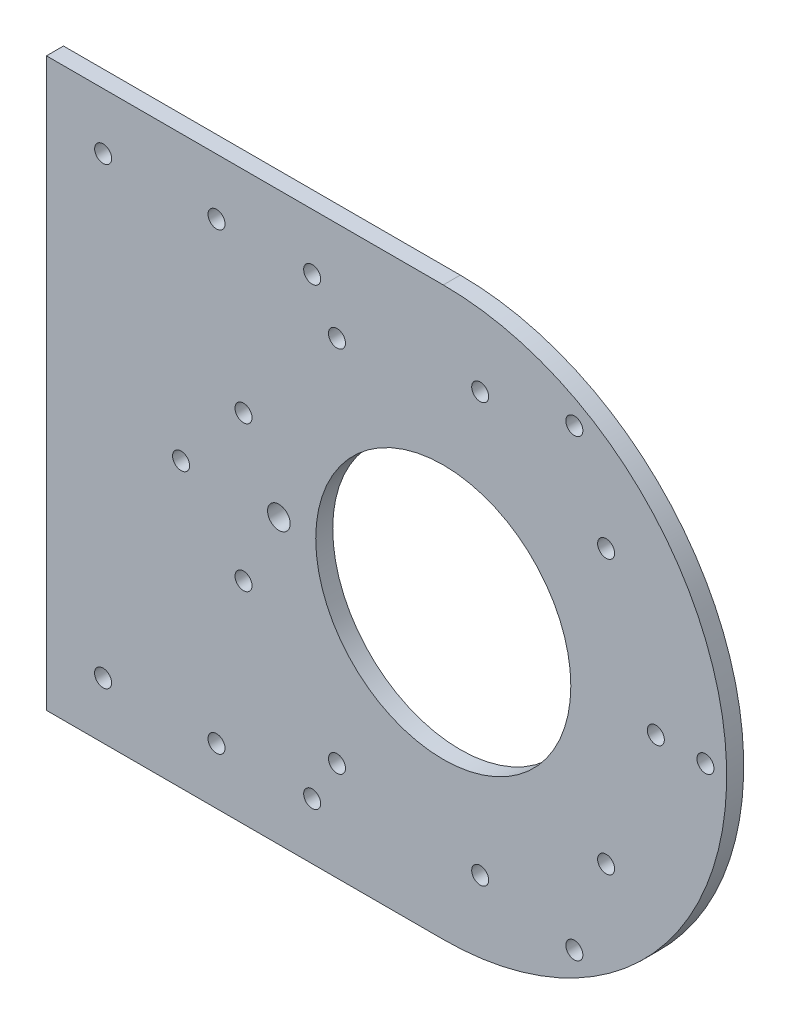
SolidWorks part; units mm, degrees
ref_plane "Front Plane" through (0, 0, 0) normal (0, 0, 1) x (1, 0, 0)
ref_plane "Top Plane" through (0, 0, 0) normal (0, 1, 0) x (1, 0, 0)
ref_plane "Right Plane" through (0, 0, 0) normal (1, 0, 0) x (0, 0, -1)
sketch "草图1" plane through (0, 0, 0) normal (0, 0, 1) x (1, 0, 0)
  line L1 (-400, 0) -> (-312.5, 0) construction
  line L3 (-10, 50) -> (-350, 50)
  line L5 (-10, -50) -> (-350, -50)
  arc A1 (-350, 50) -> (-350, -50) centre (-350, 0) ccw
  circle A2 centre (-350, 0) radius 37.5 construction
  circle A3 centre (-387.5, 0) radius 1.5
  circle A4 centre (-378.7267, 24.1045) radius 1.5
  circle A5 centre (-356.5118, 36.9303) radius 1.5
  circle A6 centre (-331.25, 32.476) radius 1.5
  circle A7 centre (-314.7615, 12.8258) radius 1.5
  circle A8 centre (-314.7615, -12.8258) radius 1.5
  circle A9 centre (-331.25, -32.476) radius 1.5
  circle A10 centre (-356.5118, -36.9303) radius 1.5
  circle A11 centre (-378.7267, -24.1045) radius 1.5
  circle A12 centre (-350, 0) radius 22.5
  circle A13 centre (-10, 0) radius 37.5 construction
  circle A14 centre (-10, 0) radius 22.5
  circle A15 centre (18.7267, -24.1045) radius 1.5
  circle A16 centre (-3.4882, -36.9303) radius 1.5
  circle A17 centre (-28.75, -32.476) radius 1.5
  circle A18 centre (-45.2385, -12.8258) radius 1.5
  circle A19 centre (-45.2385, 12.8258) radius 1.5
  circle A20 centre (-28.75, 32.476) radius 1.5
  circle A21 centre (-3.4882, 36.9303) radius 1.5
  circle A22 centre (18.7267, 24.1045) radius 1.5
  circle A23 centre (27.5, 0) radius 1.5
  arc A24 (-10, 50) -> (-10, -50) centre (-10, 0) cw
  point P5 (0, 0)
  point P30 (-350, 0)
  point P54 (-10, 0)
  dimension "D1" = 75
  dimension "D2" = 3
  dimension "D4" = 22.5
  dimension "D3" = 9
extrude "凸台-拉伸1" add sketch "草图1" along normal blind 3
sketch "草图2" plane through (0, 0, 0) normal (0, 0, -1) x (-1, 0, 0)
  circle A0 centre (10, 0) radius 29 construction
  circle A1 centre (39, 0) radius 2
  circle A2 centre (350, 0) radius 29 construction
  circle A3 centre (321, 0) radius 1.75
  dimension "D1" = 58
  dimension "D2" = 4
extrude "切除-拉伸1" cut sketch "草图2" against normal blind 10
sketch "草图3" plane through (0, 0, 0) normal (0, 0, -1) x (-1, 0, 0)
  line L0 (10, -50) -> (350, -50) construction
  line L1 (180, -50) -> (80, -50)
  line L3 (80, -50) -> (415.6006, -50)
  line L4 (80, -50) -> (80, 75.6691)
  line L5 (80, 75.6691) -> (415.6006, 75.6691)
  line L6 (415.6006, -50) -> (415.6006, 75.6691)
  circle M2 centre (321, 0) radius 1.75
  line M4 (10, -50) -> (350, -50)
  arc M5 (350, -50) -> (350, 50) centre (350, 0) ccw
  line M6 (350, 50) -> (10, 50)
  circle M12 centre (350, 0) radius 22.5
  circle M13 centre (378.7267, -24.1045) radius 1.5
  circle M14 centre (356.5118, -36.9303) radius 1.5
  circle M15 centre (331.25, -32.476) radius 1.5
  circle M16 centre (314.7615, -12.8258) radius 1.5
  circle M17 centre (314.7615, 12.8258) radius 1.5
  circle M18 centre (331.25, 32.476) radius 1.5
  circle M19 centre (356.5118, 36.9303) radius 1.5
  circle M20 centre (378.7267, 24.1045) radius 1.5
  circle M21 centre (387.5, 0) radius 1.5
  dimension "D1" = 100
extrude "切除-拉伸2" cut sketch "草图3" against normal blind 10 contours L4 M4 M5 M6 M2 M13 M15 M17 M19 M21 M20 M18 M16 M14 M12
sketch "草图4" plane through (0, 0, 0) normal (0, 0, -1) x (-1, 0, 0)
  circle A0 centre (10, 0) radius 46.25 construction
  circle A1 centre (-36.25, 0) radius 1.5
  circle A2 centre (-13.125, 40.0537) radius 1.5
  circle A3 centre (33.125, 40.0537) radius 1.5
  circle A4 centre (56.25, 0) radius 1.5
  circle A5 centre (33.125, -40.0537) radius 1.5
  circle A6 centre (-13.125, -40.0537) radius 1.5
  point P17 (10, 0)
  dimension "D1" = 92.5
  dimension "D2" = 3
  dimension "D3" = 6
extrude "切除-拉伸3" cut sketch "草图4" against normal blind 10
sketch "草图5" plane through (0, 0, 3) normal (0, 0, 1) x (1, 0, 0)
  circle A0 centre (-70, 40.052) radius 1.5
  circle A1 centre (-50, 40.052) radius 1.5
  circle A2 centre (-70.014, -40.0488) radius 1.5
  circle A3 centre (-50, -40.0488) radius 1.5
  dimension "D1" = 3
extrude "切除-拉伸4" cut sketch "草图5" against normal through all
